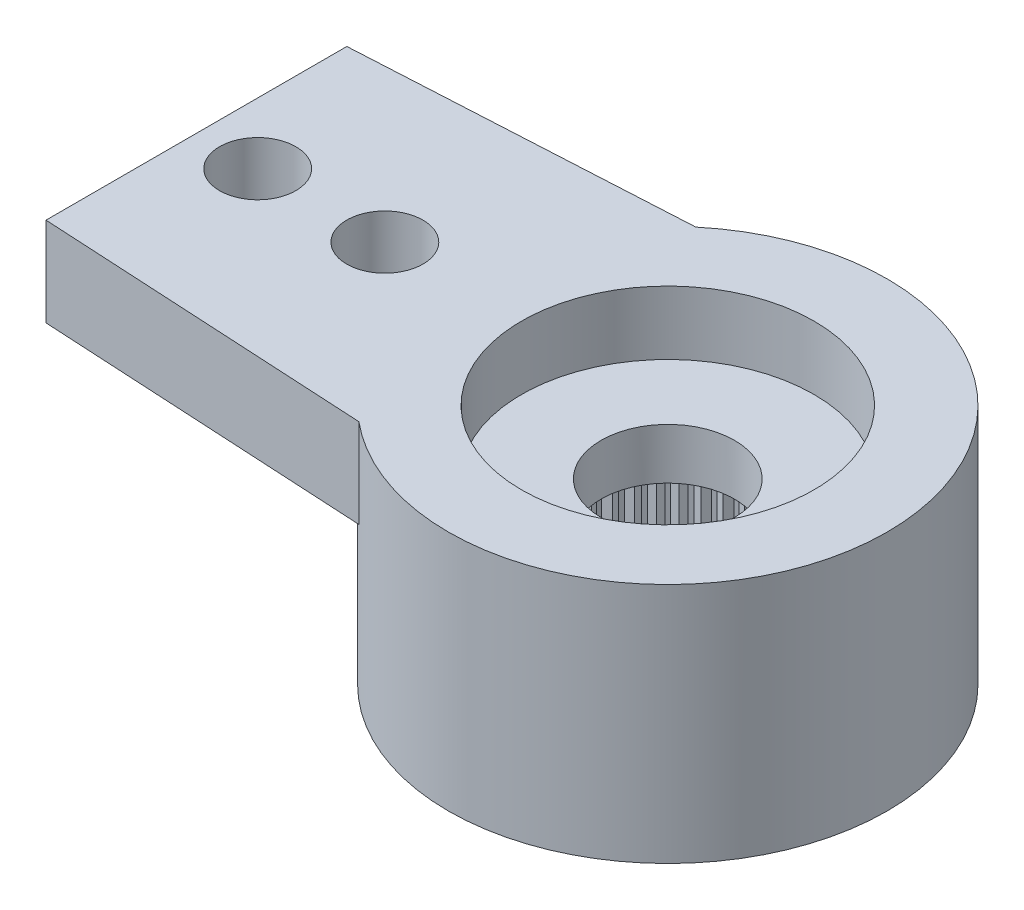
SolidWorks part; units mm, degrees
material "PVC Rígido"
ref_plane "Plano frontal" through (0, 0, 0) normal (0, 0, 1) x (1, 0, 0)
ref_plane "Plano superior" through (0, 0, 0) normal (0, 1, 0) x (1, 0, 0)
ref_plane "Plano direito" through (0, 0, 0) normal (1, 0, 0) x (0, 0, -1)
sketch "Esboço1" plane through (0, 0, 0) normal (0, 1, 0) x (1, 0, 0)
  line L0 (0, 0) -> (-14.05, 0) construction
  line L1 (-14.1591, 1.997) -> (-2.2091, 2.65)
  line L2 (-2.2091, -2.65) -> (-14.1591, -1.997)
  arc A0 (-2.2091, -2.65) -> (-2.2091, 2.65) centre (0, 0) ccw
  arc A1 (-14.1591, 1.997) -> (-14.1591, -1.997) centre (-14.05, 0) ccw
  dimension "D1" = 6.9
  dimension "D2" = 4
  dimension "D3" = 19.5
  dimension "D4" = 5.3
extrude "Ressalto-extrusão1" add sketch "Esboço1" against normal blind 1.4
sketch "Esboço2" plane through (0, -1.4, 0) normal (0, -1, 0) x (1, 0, 0)
  arc A0 (-2.2091, -2.65) -> (-2.2091, 2.65) centre (0, 0) ccw construction
  circle A1 centre (0, 0) radius 3.45
extrude "Ressalto-extrusão2" add sketch "Esboço2" along normal offset from surface (2.4 mm away) 3.8 up to face at (-7.242, 0, 0)
hole_wizard "Furo4" positions "Esboço9" profile "Esboço10" legacy end condition through all
sketch "Esboço9" plane through (0, 0, 0) normal (0, 1, 0) x (1, 0, 0)
  line L1 (-14.45, 0) -> (0, 0) construction
  arc A2 (-14.1591, 1.997) -> (-14.1591, -1.997) centre (-14.05, 0) ccw construction
  point P0 (-14.45, 0)
  point P19 (-16.05, 0)
  dimension "D1" = 1.6
sketch "Esboço10" plane through (-14.45, 0, 0) normal (1, 0, 0) x (0, 0, 1)
  line L0 (0, 0) -> (0, 3.8)
  line L1 (0, 3.8) -> (0.6, 3.8)
  line L2 (0.6, 3.8) -> (0.6, 0)
  line L3 (0.6, 0) -> (0, 0)
  line L4 (0, 110) -> (0, -10) construction
  dimension "Diameter" = 1.2
  dimension "Depth" = 3.8
pattern_linear "Padrão linear1" count 6 spacing 2 along (1, 0, 0) of "Furo4"
hole_wizard "Furo1" positions "Esboço3" profile "Esboço4" legacy
sketch "Esboço3" plane through (0, -3.8, 0) normal (0, -1, 0) x (-1, 0, 0)
  point P0 (0, 0)
sketch "Esboço4" plane through (0, -3.8, 0) normal (1, 0, 0) x (0, 0, -1)
  line L0 (0, 0) -> (0, 2)
  line L1 (0, 2) -> (2.475, 2)
  line L2 (2.475, 2) -> (2.475, 0)
  line L3 (2.475, 0) -> (0, 0)
  line L4 (0, 110) -> (0, -10) construction
  dimension "Diameter" = 4.95
  dimension "Depth" = 2
hole_wizard "Furo2" positions "Esboço5" profile "Esboço6" legacy
sketch "Esboço5" plane through (0, 0, 0) normal (0, 1, 0) x (1, 0, 0)
  point P0 (0, 0)
sketch "Esboço6" plane through (0, 0, 0) normal (1, 0, 0) x (0, 0, 1)
  line L0 (0, 0) -> (0, 1)
  line L1 (0, 1) -> (2.3, 1)
  line L2 (2.3, 1) -> (2.3, 0)
  line L3 (2.3, 0) -> (0, 0)
  line L4 (0, 110) -> (0, -10) construction
  dimension "Diameter" = 4.6
  dimension "Depth" = 1
hole_wizard "Furo3" positions "Esboço7" profile "Esboço8" legacy end condition through all
sketch "Esboço7" plane through (0, 0, 0) normal (0, 1, 0) x (1, 0, 0)
  point P0 (0, 0)
sketch "Esboço8" plane through (0, 0, 0) normal (1, 0, 0) x (0, 0, 1)
  line L0 (0, 0) -> (0, 3.8)
  line L1 (0, 3.8) -> (1.05, 3.8)
  line L2 (1.05, 3.8) -> (1.05, 0)
  line L3 (1.05, 0) -> (0, 0)
  line L4 (0, 110) -> (0, -10) construction
  dimension "Diameter" = 2.1
  dimension "Depth" = 3.8
sketch "Esboço11" plane through (0, -3.8, 0) normal (0, -1, 0) x (1, 0, 0)
  line L0 (-0.0981, 2.4731) -> (0, 2.375)
  line L1 (0, 2.375) -> (0.0981, 2.4731)
  line L2 (0, 0) -> (0, 2.475) construction
  circle A0 centre (0, 0) radius 2.375 construction
  circle A1 centre (0, 0) radius 2.475
  arc A2 (0.0981, 2.4731) -> (-0.0981, 2.4731) centre (0, 0) ccw
  dimension "D3" = 4.75
  dimension "D2" = 0.1
  dimension "D1" = 0
extrude "Ressalto-extrusão3" add sketch "Esboço11" against normal up to surface (2 mm away) up to face at (0, -1.8, 1.05)
pattern_circular "PadrãoCircular1" count 60 over 360 about axis through (0, 0, 0) along (0, 1, 0) of "Ressalto-extrusão3"
sketch "Sketch1" plane through (0, 0, 0) normal (0, 1, 0) x (1, 0, 0)
  line L1 (-7.4137, -4.2763) -> (-16.2815, -4.2763)
  line L2 (-7.4137, -4.2763) -> (-7.4137, 3.4567)
  line L3 (-7.4137, 3.4567) -> (-16.2815, 3.4567)
  line L4 (-16.2815, -4.2763) -> (-16.2815, 3.4567)
extrude "Cut-Extrude1" cut sketch "Sketch1" against normal through all both
